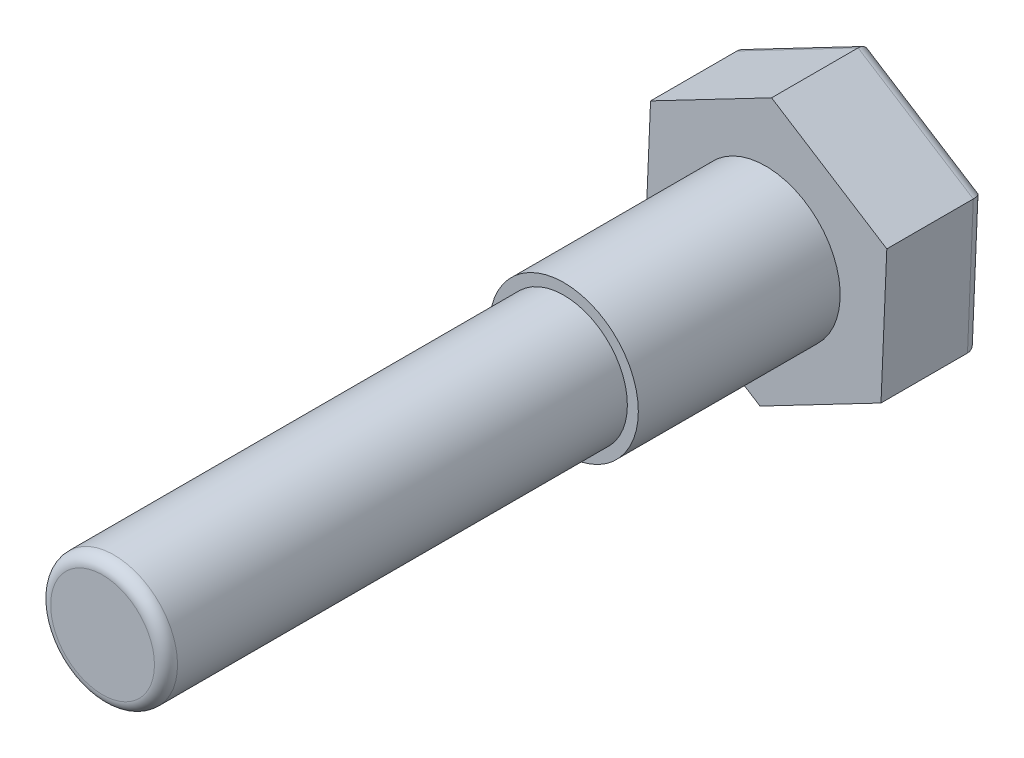
SolidWorks part; units mm, degrees
ref_plane "前视" through (0, 0, 0) normal (0, 0, 1) x (1, 0, 0)
ref_plane "上视" through (0, 0, 0) normal (0, 1, 0) x (1, 0, 0)
ref_plane "右视" through (0, 0, 0) normal (1, 0, 0) x (0, 0, -1)
sketch "草图1" plane through (0, 0, 0) normal (0, 0, 1) x (1, 0, 0)
  line L1 (20.9842, 10.9543) -> (1.0054, 23.65)
  line L2 (1.0054, 23.65) -> (-19.9788, 12.6957)
  line L3 (-19.9788, 12.6957) -> (-20.9842, -10.9543)
  line L4 (-20.9842, -10.9543) -> (-1.0054, -23.65)
  line L5 (-1.0054, -23.65) -> (19.9788, -12.6957)
  line L6 (19.9788, -12.6957) -> (20.9842, 10.9543)
  circle A0 centre (0, 0) radius 20.5 construction
  dimension "D1" = 47.3
  dimension "D2" = 41
extrude "基体-拉伸" add sketch "草图1" along normal blind 17
sketch "草图2" plane through (0, 0, 17) normal (0, 0, 1) x (1, 0, 0)
  circle A0 centre (0, 0) radius 12.9
  dimension "D1" = 25.8
extrude "凸台-拉伸1" add sketch "草图2" along normal blind 35
fillet "圆角3" radius 2 6 edges at (9.4867, -18.1729, 0) (-10.9948, -17.3021, 0) (-20.4815, 0.8707, 0) (-9.4867, 18.1729, 0) (10.9948, 17.3021, 0) (20.4815, -0.8707, 0)
sketch "草图3" plane through (0, 0, 52) normal (0, 0, 1) x (1, 0, 0)
  circle A0 centre (0, 0) radius 11
  dimension "D1" = 22
extrude "凸台-拉伸2" add sketch "草图3" along normal blind 80
fillet "圆角4" radius 2 1 edges at (11, 0, 132)
